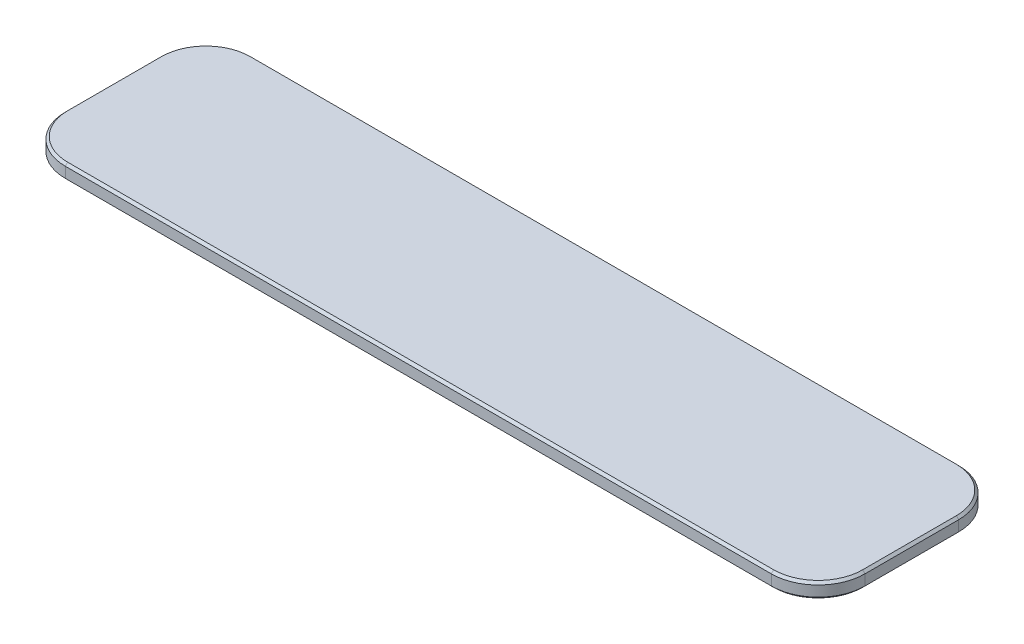
SolidWorks part; units mm, degrees
ref_plane "Front" through (0, 0, 0) normal (0, 0, 1) x (1, 0, 0)
ref_plane "Top" through (0, 0, 0) normal (0, 1, 0) x (1, 0, 0)
ref_plane "Right" through (0, 0, 0) normal (1, 0, 0) x (0, 0, -1)
sketch "Sketch1" plane through (0, 0, 0) normal (0, 1, 0) x (1, 0, 0)
  line L1 (-170.675, -40) -> (170.675, -40)
  line L2 (-170.675, -40) -> (-170.675, 40)
  line L3 (-170.675, 40) -> (170.675, 40)
  line L4 (170.675, -40) -> (170.675, 40)
  line L5 (-170.675, -40) -> (170.675, 40) construction
  line L6 (-170.675, 40) -> (170.675, -40) construction
  point P0 (0, 0)
  dimension "D1" = 80
  dimension "D2" = 341.35
extrude "Boss-Extrude1" add sketch "Sketch1" along normal blind 6.5
fillet "Fillet1" radius 20 4 edges at (170.675, 3.25, 40) (-170.675, 3.25, -40) (170.675, 3.25, -40) (-170.675, 3.25, 40)
chamfer "Chamfer1" distance 1 angle 45 16 edges at (164.8171, 0, -34.1421) (0, 0, -40) (-164.8171, 0, -34.1421) (-170.675, 0, 0) (-164.8171, 0, 34.1421) (0, 0, 40) (164.8171, 0, 34.1421) (170.675, 0, 0) (-164.8171, 6.5, 34.1421) (-170.675, 6.5, 0) (-164.8171, 6.5, -34.1421) (0, 6.5, -40) (164.8171, 6.5, -34.1421) (170.675, 6.5, 0) (164.8171, 6.5, 34.1421) (0, 6.5, 40)
